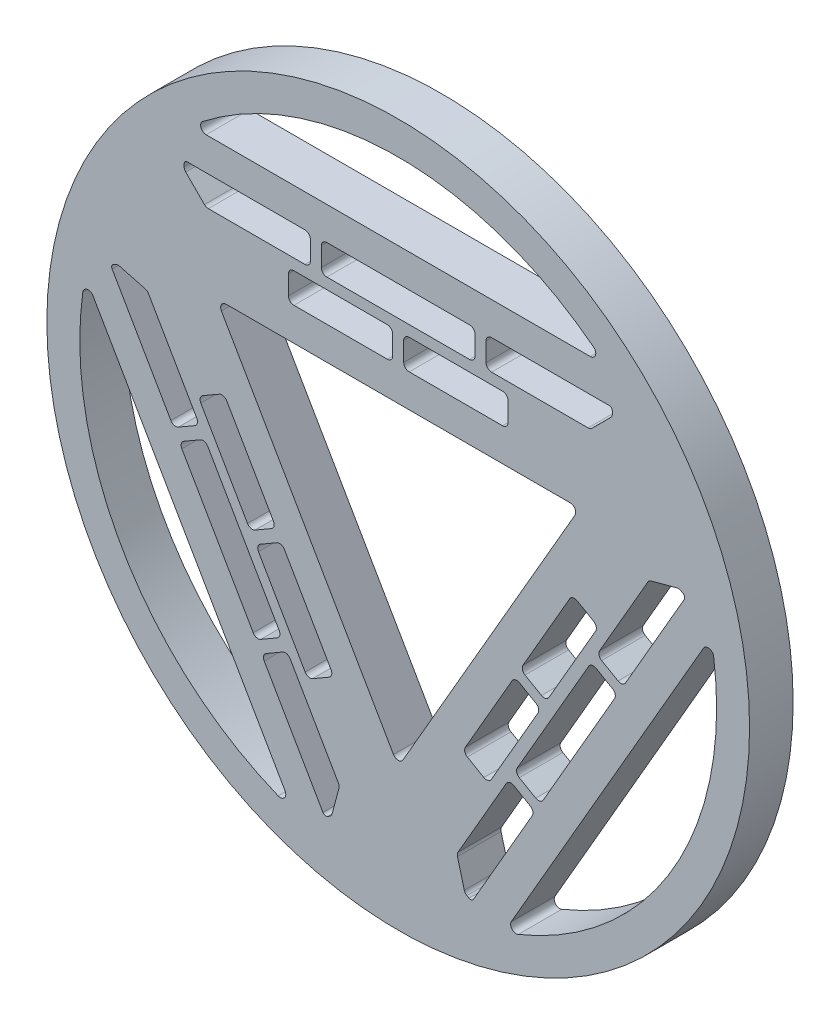
SolidWorks part; units mm, degrees
ref_plane "前基準面" through (0, 0, 0) normal (0, 0, 1) x (1, 0, 0)
ref_plane "上基準面" through (0, 0, 0) normal (0, 1, 0) x (1, 0, 0)
ref_plane "右基準面" through (0, 0, 0) normal (1, 0, 0) x (0, 0, -1)
sketch "Sketch2" plane through (0, 0, 0) normal (0, 0, 1) x (1, 0, 0)
  line L0 (0, 0) -> (0, 26.428) construction
  line L1 (0, 0) -> (22.8874, -13.214) construction
  line L2 (0, 0) -> (-22.8874, -13.214) construction
  line L3 (-4.8027, -13.6815) -> (-14.2499, 2.6815)
  line L4 (-16.1555, 10) -> (16.1555, 10) construction
  line L5 (13.1022, 3.6937) -> (6.4772, -7.7811)
  line L6 (-0.5825, -18.9911) -> (-16.738, 8.9911) construction
  line L7 (-10, 5.7735) -> (10, 5.7735) construction
  line L8 (10, 5.7735) -> (0, -11.547) construction
  line L9 (14.2499, 2.6815) -> (4.8027, -13.6815)
  line L10 (-5, 6.2735) -> (-0.25, 6.2735)
  line L11 (16.738, 8.9911) -> (0.5825, -18.9911) construction
  line L12 (0, -11.547) -> (-10, 5.7735) construction
  line L13 (-10, 5.7735) -> (5, -2.8868) construction
  line L14 (10, 5.7735) -> (-5, -2.8868) construction
  line L15 (7.933, 1.1934) -> (5.558, -2.9202)
  line L19 (0, -9.547) -> (-8.2679, 4.7735)
  line L20 (-8.2679, 4.7735) -> (8.2679, 4.7735)
  line L21 (8.2679, 4.7735) -> (0, -9.547)
  line L22 (-2.933, -7.4669) -> (-5.308, -3.3533)
  line L23 (5.433, -3.1368) -> (8.2272, -4.75) construction
  line L24 (2.1716, -12.5121) -> (3.3522, -13.1937)
  line L25 (11.9216, 4.3754) -> (13.1022, 3.6937)
  line L26 (11.7051, 4.5004) -> (1.9551, -12.3871) construction
  line L27 (8.2272, -4.75) -> (6.8301, -3.9434) construction
  line L28 (9.9772, -1.7189) -> (8.7966, -1.0373)
  line L29 (6.4772, -7.7811) -> (5.2966, -7.0995)
  line L30 (9.9772, -1.7189) -> (6.4772, -7.7811)
  line L31 (8.5801, -0.9123) -> (5.0801, -6.9745) construction
  line L32 (8.3636, -0.7873) -> (6.7386, -3.6019)
  line L33 (8.7966, -1.0373) -> (5.2966, -7.0995)
  line L34 (9.9772, -1.7189) -> (8.5801, -0.9123) construction
  line L35 (6.4772, -7.7811) -> (5.0801, -6.9745) construction
  line L36 (10.2272, -1.2859) -> (9.0466, -0.6043)
  line L37 (6.2272, -8.2141) -> (5.0466, -7.5325)
  line L38 (5.0466, -7.5325) -> (2.1716, -12.5121)
  line L39 (9.0466, -0.6043) -> (11.9216, 4.3754)
  line L40 (6.6136, -3.8184) -> (5.433, -3.1368) construction
  line L41 (9.1136, 0.5118) -> (7.933, 1.1934)
  line L42 (4.1136, -8.1485) -> (2.933, -7.4669)
  line L43 (8.3636, -0.7873) -> (9.1136, 0.5118)
  line L44 (4.8636, -6.8495) -> (4.1136, -8.1485)
  line L45 (5.433, -3.1368) -> (6.6136, -3.8184) construction
  line L46 (5.308, -3.3533) -> (6.4886, -4.0349)
  line L47 (5.558, -2.9202) -> (6.7386, -3.6019)
  line L48 (10.308, 5.307) -> (13.1022, 3.6937) construction
  line L49 (0.558, -11.5805) -> (3.3522, -13.1937) construction
  line L52 (6.2272, -8.2141) -> (3.3522, -13.1937)
  line L53 (13.1022, 3.6937) -> (10.2272, -1.2859)
  line L54 (5.308, -3.3533) -> (2.933, -7.4669)
  line L55 (6.4886, -4.0349) -> (4.8636, -6.8495)
  line L56 (10.866, 6.2735) -> (0, -12.547) construction
  line L57 (13.1022, 3.6937) -> (10.2272, -1.2859)
  line L58 (8.3636, -0.7873) -> (4.8636, -6.8495) construction
  line L59 (-10.2272, -1.2859) -> (-13.1022, 3.6937)
  line L60 (-11.9216, 4.3754) -> (-13.1022, 3.6937)
  line L61 (-9.0466, -0.6043) -> (-11.9216, 4.3754)
  line L62 (-9.9772, -1.7189) -> (-8.7966, -1.0373)
  line L64 (-5.2966, -7.0995) -> (-8.7966, -1.0373)
  line L65 (-6.4772, -7.7811) -> (-5.2966, -7.0995)
  line L66 (-2.1716, -12.5121) -> (-3.3522, -13.1937)
  line L67 (-5.0466, -7.5325) -> (-2.1716, -12.5121)
  line L68 (-6.2272, -8.2141) -> (-5.0466, -7.5325)
  line L69 (-4.1136, -8.1485) -> (-2.933, -7.4669)
  line L70 (-2.933, -7.4669) -> (-5.308, -3.3533)
  line L71 (-5.308, -3.3533) -> (-6.4886, -4.0349)
  line L72 (-4.8636, -6.8495) -> (-6.4886, -4.0349)
  line L73 (-5.558, -2.9202) -> (-6.7386, -3.6019)
  line L74 (-5.558, -2.9202) -> (-7.933, 1.1934)
  line L75 (-9.1136, 0.5118) -> (-7.933, 1.1934)
  line L76 (-8.3636, -0.7873) -> (-9.1136, 0.5118)
  line L77 (-6.7386, -3.6019) -> (-8.3636, -0.7873)
  line L78 (4, 9.5) -> (9.75, 9.5)
  line L79 (9.75, 8.1368) -> (9.75, 9.5)
  line L80 (4, 8.1368) -> (9.75, 8.1368)
  line L81 (3.5, 9.5) -> (3.5, 8.1368)
  line L83 (-3.5, 8.1368) -> (3.5, 8.1368)
  line L84 (-3.5, 9.5) -> (-3.5, 8.1368)
  line L85 (-9.75, 8.1368) -> (-9.75, 9.5)
  line L86 (-4, 8.1368) -> (-9.75, 8.1368)
  line L87 (-4, 9.5) -> (-4, 8.1368)
  line L88 (-5, 7.6368) -> (-5, 6.2735)
  line L89 (-5, 6.2735) -> (-0.25, 6.2735)
  line L90 (-0.25, 6.2735) -> (-0.25, 7.6368)
  line L91 (-3.5, 7.6368) -> (-0.25, 7.6368)
  line L92 (0.25, 6.2735) -> (0.25, 7.6368)
  line L93 (0.25, 6.2735) -> (5, 6.2735)
  line L94 (5, 7.6368) -> (5, 6.2735)
  line L95 (3.5, 7.6368) -> (5, 7.6368)
  line L96 (0.25, 7.6368) -> (3.5, 7.6368)
  line L97 (-4.8636, -6.8495) -> (-4.1136, -8.1485)
  line L98 (-9.0466, -0.6043) -> (-10.2272, -1.2859)
  line L99 (-3.5, 7.6368) -> (-5, 7.6368)
  line L100 (4, 9.5) -> (4, 8.1368)
  line L101 (-3.5, 9.5) -> (3.5, 9.5)
  line L102 (-3.5, 9.5) -> (3.5, 9.5)
  line L104 (4, 9.5) -> (9.75, 9.5)
  line L105 (0.25, 6.2735) -> (5, 6.2735)
  line L106 (-10.866, 6.2735) -> (10.866, 6.2735) construction
  line L107 (0, -12.547) -> (-10.866, 6.2735) construction
  line L108 (-10.2272, -1.2859) -> (-16.1645, 8.9977)
  line L110 (-5.558, -2.9202) -> (-7.933, 1.1934)
  line L111 (-6.4772, -7.7811) -> (-9.9772, -1.7189)
  line L112 (-6.4772, -7.7811) -> (-9.9772, -1.7189)
  line L113 (-3.3522, -13.1937) -> (-6.2272, -8.2141)
  line L114 (-3.3522, -13.1937) -> (-6.2272, -8.2141)
  line L115 (-9.75, 9.5) -> (-4, 9.5)
  line L116 (-9.75, 9.5) -> (-4, 9.5)
  line L117 (-9.4472, 11) -> (9.4472, 11)
  line L119 (-14.6969, 9.5) -> (-12.8744, 9.5) [skipped]
  line L120 (-0.29, -18.4977) -> (-0.8788, -17.4779) [skipped]
  circle A0 centre (0, 0) radius 22.5 construction
  arc A1 (9.4472, 11) -> (-9.4472, 11) centre (0, 0) ccw
  circle A2 centre (0, 0) radius 14.5 construction
  arc A4 (-14.2499, 2.6815) -> (-4.8027, -13.6815) centre (0, 0) ccw
  circle A8 centre (0, 0) radius 19 construction
  circle A9 centre (0, 0) radius 17.5 construction
  circle A10 centre (0, 0) radius 16
  arc A11 (4.8027, -13.6815) -> (14.2499, 2.6815) centre (0, 0) ccw
  point P19 (0, 0)
  dimension "D3" = 3
  dimension "D5" = 45
  dimension "D6" = 3.5
  dimension "D12" = 4.2265
  dimension "D19" = 0.5
  dimension "D21" = 5
  dimension "D4" = 1.5
  dimension "D7" = 1.5
  dimension "D8" = 1.5
  dimension "D9" = 1.5
  dimension "D11" = 1
  dimension "D13" = 9.75
  dimension "D14" = 9.75
  dimension "D15" = 3.5
  dimension "D16" = 0.25
  dimension "D17" = 0.25
  dimension "D18" = 0.25
  dimension "D20" = 0.5
  dimension "D22" = 5
  dimension "D23" = 0.25
  dimension "D2" = 3
extrude "Boss-Extrude1" add sketch "Sketch2" along normal blind 1.9844
fillet "Fillet1" radius 0.25 6 edges at (4.8027, -13.6815, 0.9922) (14.2499, 2.6815, 0.9922) (-14.2499, 2.6815, 0.9922) (-4.8027, -13.6815, 0.9922) (9.4472, 11, 0.9922) (-9.4472, 11, 0.9922)
fillet "Fillet2" radius 0.25 3 edges at (0, -9.547, 0.9922) (-8.2679, 4.7735, 0.9922) (8.2679, 4.7735, 0.9922)
chamfer "Chamfer1" distance 1 6 edges at (-9.75, 8.1368, 0.9922) (9.75, 8.1368, 0.9922) (11.9216, 4.3754, 0.9922) (2.1716, -12.5121, 0.9922) (-2.1716, -12.5121, 0.9922) (-11.9216, 4.3754, 0.9922)
fillet "Fillet3" radius 0.15 6 edges at (-13.1022, 3.6937, 0.9922) (-3.3522, -13.1937, 0.9922) (9.75, 9.5, 0.9922) (13.1022, 3.6937, 0.9922) (3.3522, -13.1937, 0.9922) (-9.75, 9.5, 0.9922)
fillet "Fillet4" radius 0.25 20 edges at (5, 6.2735, 0.9922) (0.25, 6.2735, 0.9922) (5, 7.6368, 0.9922) (0.25, 7.6368, 0.9922) (-0.25, 6.2735, 0.9922) (-5, 6.2735, 0.9922) (-0.25, 7.6368, 0.9922) (-5, 7.6368, 0.9922) (-4, 8.1368, 0.9922) (-4, 9.5, 0.9922) (-9.75, 9.1368, 0.9922) (-8.75, 8.1368, 0.9922) (-3.5, 8.1368, 0.9922) (-3.5, 9.5, 0.9922) (3.5, 8.1368, 0.9922) (3.5, 9.5, 0.9922) (4, 8.1368, 0.9922) (4, 9.5, 0.9922) (8.75, 8.1368, 0.9922) (9.75, 9.1368, 0.9922)
fillet "Fillet5" radius 0.25 20 edges at (5.308, -3.3533, 0.9922) (2.933, -7.4669, 0.9922) (4.1136, -8.1485, 0.9922) (6.4886, -4.0349, 0.9922) (10.2272, -1.2859, 0.9922) (9.0466, -0.6043, 0.9922) (6.7386, -3.6019, 0.9922) (9.1136, 0.5118, 0.9922) (7.933, 1.1934, 0.9922) (5.558, -2.9202, 0.9922) (5.0466, -7.5325, 0.9922) (6.2272, -8.2141, 0.9922) (8.7966, -1.0373, 0.9922) (5.2966, -7.0995, 0.9922) (6.4772, -7.7811, 0.9922) (9.9772, -1.7189, 0.9922) (12.7877, 3.8754, 0.9922) (11.4216, 3.5093, 0.9922) (2.6716, -11.6461, 0.9922) (3.0377, -13.0121, 0.9922)
fillet "Fillet6" radius 0.25 20 edges at (-6.2272, -8.2141, 0.9922) (-6.4886, -4.0349, 0.9922) (-9.9772, -1.7189, 0.9922) (-9.1136, 0.5118, 0.9922) (-4.1136, -8.1485, 0.9922) (-6.4772, -7.7811, 0.9922) (-6.7386, -3.6019, 0.9922) (-10.2272, -1.2859, 0.9922) (-2.6716, -11.6461, 0.9922) (-5.2966, -7.0995, 0.9922) (-2.933, -7.4669, 0.9922) (-5.558, -2.9202, 0.9922) (-9.0466, -0.6043, 0.9922) (-11.4216, 3.5093, 0.9922) (-8.7966, -1.0373, 0.9922) (-7.933, 1.1934, 0.9922) (-5.308, -3.3533, 0.9922) (-5.0466, -7.5325, 0.9922) (-3.0377, -13.0121, 0.9922) (-12.7877, 3.8754, 0.9922)
